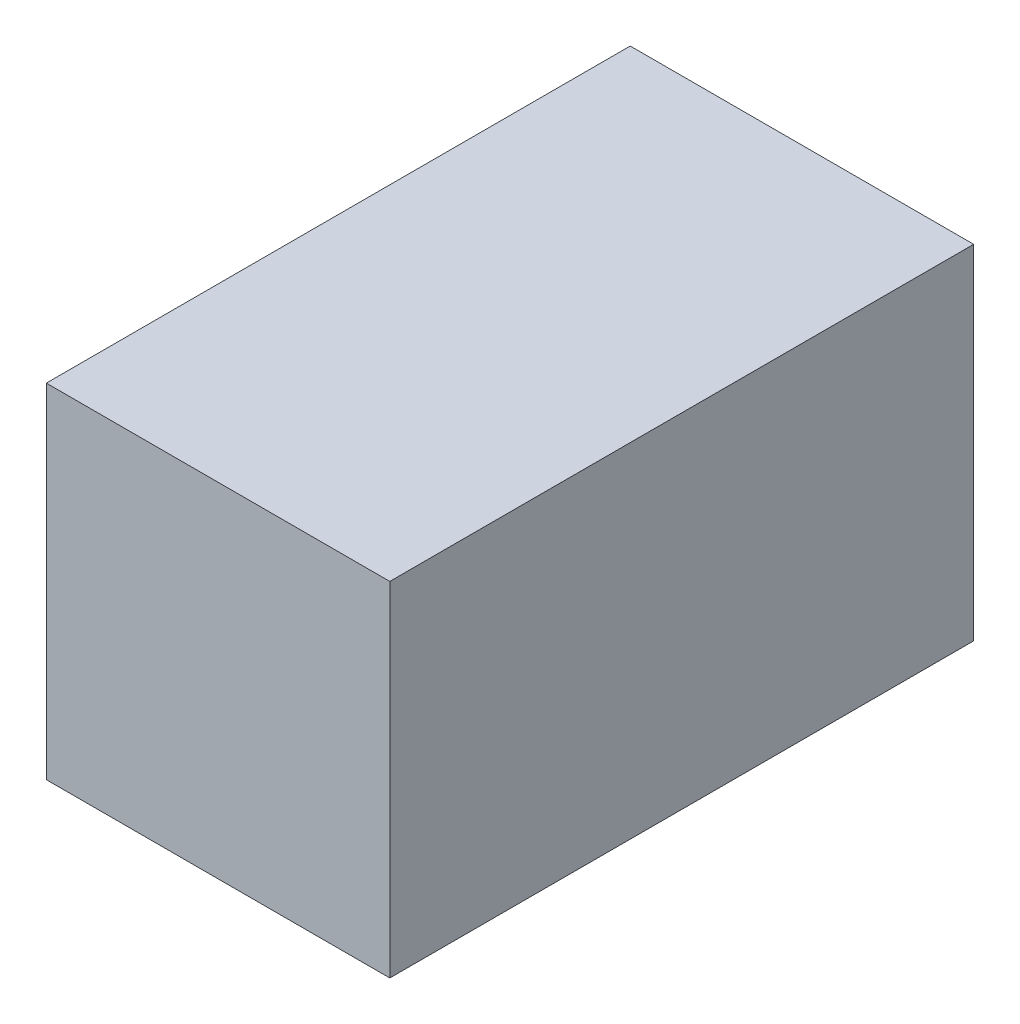
SolidWorks part; units mm, degrees
ref_plane "Front Plane" through (0, 0, 0) normal (0, 0, 1) x (1, 0, 0)
ref_plane "Top Plane" through (0, 0, 0) normal (0, 1, 0) x (1, 0, 0)
ref_plane "Right Plane" through (0, 0, 0) normal (1, 0, 0) x (0, 0, -1)
sketch "Sketch1" plane through (0, 0, 0) normal (0, 0, 1) x (1, 0, 0)
  line L1 (-100, -100) -> (100, -100)
  line L2 (-100, -100) -> (-100, 100)
  line L3 (-100, 100) -> (100, 100)
  line L4 (100, -100) -> (100, 100)
  line L5 (-100, -100) -> (100, 100) construction
  line L6 (-100, 100) -> (100, -100) construction
  point P0 (0, 0)
  dimension "D1" = 200
  dimension "D2" = 200
extrude "Boss-Extrude1" add sketch "Sketch1" along normal blind 340
other "Cavity5"
other "Part1<1>@Assem15"
